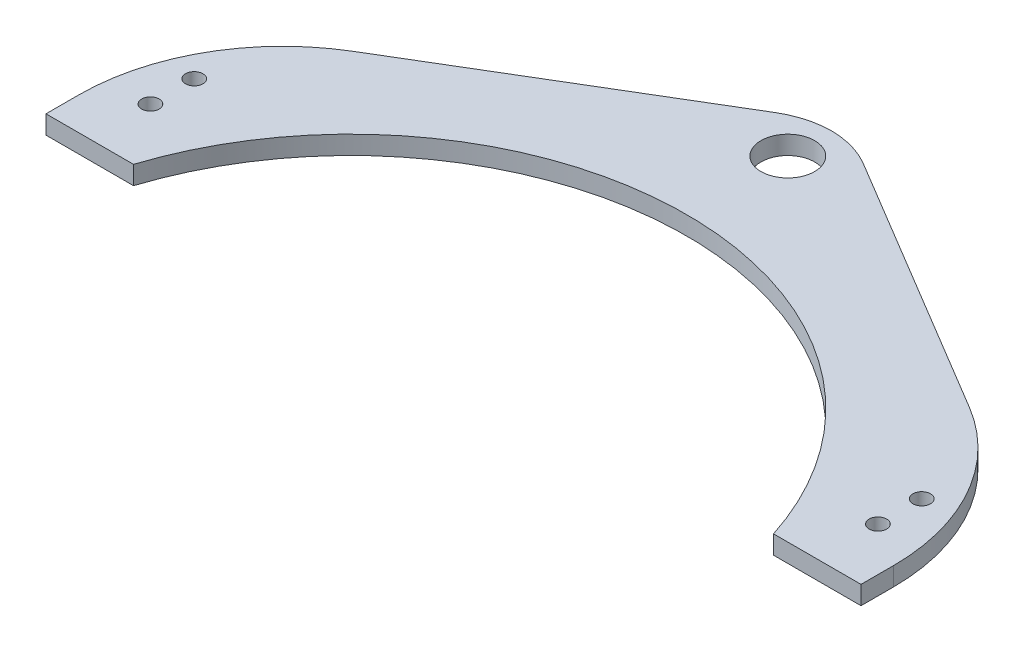
SolidWorks part; units mm, degrees
ref_plane "Front Plane" through (0, 0, 0) normal (0, 0, 1) x (1, 0, 0)
ref_plane "Top Plane" through (0, 0, 0) normal (0, 1, 0) x (1, 0, 0)
ref_plane "Right Plane" through (0, 0, 0) normal (1, 0, 0) x (0, 0, -1)
sketch "Sketch1" plane through (0, 0, 0) normal (0, 1, 0) x (1, 0, 0)
  line L1 (54.85, 0) -> (54.85, 39.9)
  line L2 (109.7, 0) -> (124.7, 0)
  line L3 (0, 0) -> (-15, 0)
  line L4 (124.7, 0) -> (124.7, 16.895)
  line L5 (-15, 0) -> (-15, 16.895)
  line L6 (54.85, 0) -> (54.85, 57.3)
  line L7 (54.85, 57.3) -> (54.85, 64.8)
  line L8 (54.85, 64.8) -> (54.7052, 64.8)
  line L9 (54.85, 64.8) -> (54.9948, 64.8)
  line L10 (62.4068, 62.6719) -> (117.4016, 29.7668)
  line L11 (47.2932, 62.6719) -> (-7.7016, 29.7668)
  line L12 (117.2, 0) -> (117.2, 10.4)
  line L13 (117.2, 10.4) -> (117.2, 17.9)
  line L14 (-7.5, 0) -> (-7.5, 10.4)
  line L15 (107.6704, 35.5893) -> (62.4068, 62.6719)
  line L16 (124.7, 5.5549) -> (124.7, 0)
  line L17 (47.2932, 62.6719) -> (2.0296, 35.5893)
  line L18 (-15, 5.5549) -> (-15, 0)
  line L19 (-7.5, 10.4) -> (-7.5, 17.9)
  circle A1 centre (54.85, 57.3) radius 4.6
  arc A2 (54.7052, 64.8) -> (62.4068, 62.6719) centre (54.7052, 49.8) cw
  arc A3 (54.9948, 64.8) -> (47.2932, 62.6719) centre (54.9948, 49.8) ccw
  arc A4 (-15, 16.895) -> (-7.7016, 29.7668) centre (0, 16.895) cw
  arc A5 (124.7, 16.895) -> (117.4016, 29.7668) centre (109.7, 16.895) ccw
  circle A6 centre (117.2, 17.9) radius 1.5
  circle A7 centre (117.2, 10.4) radius 1.5
  arc A10 (107.6704, 35.5893) -> (124.7, 5.5549) centre (89.7, 5.5549) cw
  arc A11 (2.0296, 35.5893) -> (-15, 5.5549) centre (20, 5.5549) ccw
  circle A13 centre (-7.5, 17.9) radius 1.5
  circle A14 centre (-7.5, 10.4) radius 1.5
  arc A15 (0, 0) -> (109.7, 0) centre (54.85, -17.6788) cw
  point P17 (58.85, 64.8)
  point P20 (50.85, 64.8)
  point P23 (-15, 25.4)
  point P26 (124.7, 25.4)
  point P41 (124.7, 25.4)
  point P44 (-15, 25.4)
  dimension "D8" = 7.5
  dimension "D11" = 15
  dimension "D12" = 15
  dimension "D15" = 10.4
  dimension "D16" = 35
  dimension "D17" = 7.5
  dimension "D1" = 109.7
  dimension "D2" = 39.9
  dimension "D3" = 15
  dimension "D4" = 15
  dimension "D5" = 25.4
  dimension "D6" = 25.4
  dimension "D7" = 57.3
  dimension "D9" = 4
  dimension "D10" = 4
  dimension "D13" = 10.4
  dimension "D14" = 7.5
extrude "Boss-Extrude2" add sketch "Sketch1" along normal blind 3.175
